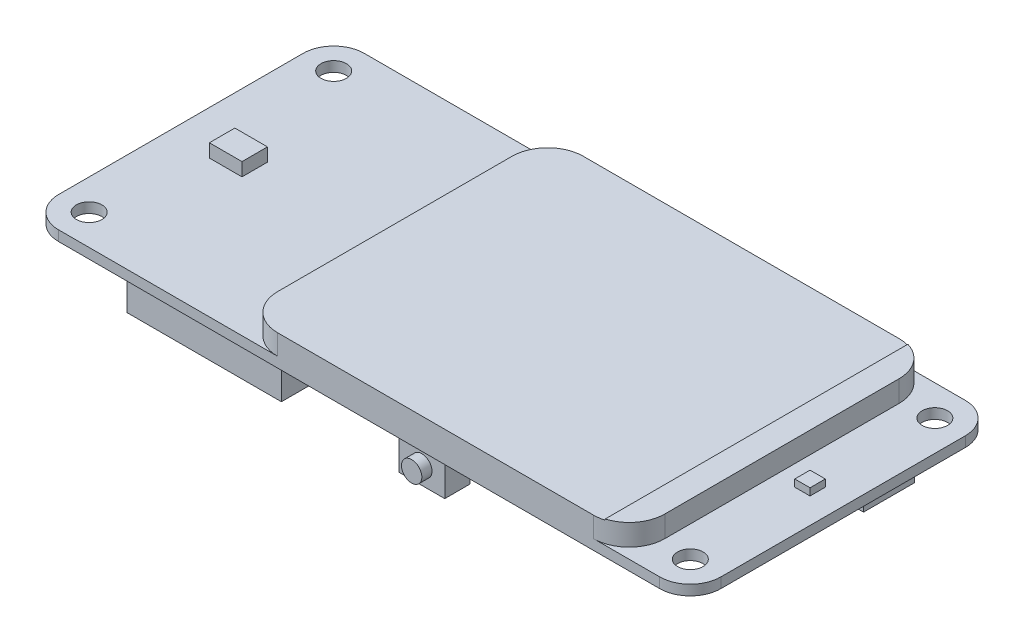
SolidWorks part; units mm, degrees
ref_plane "前视基准面" through (0, 0, 0) normal (0, 0, 1) x (1, 0, 0)
ref_plane "上视基准面" through (0, 0, 0) normal (0, 1, 0) x (1, 0, 0)
ref_plane "右视基准面" through (0, 0, 0) normal (1, 0, 0) x (0, 0, -1)
other "Configuration Table"
sketch "草图1" plane through (0, 0, 0) normal (0, 1, 0) x (1, 0, 0)
  line L1 (-29.5, 15) -> (29.5, 15)
  line L2 (-32.5, 12) -> (-32.5, -12)
  line L3 (-29.5, -15) -> (29.5, -15)
  line L4 (32.5, 12) -> (32.5, -12)
  line L5 (-32.5, 15) -> (32.5, -15) construction
  line L6 (-32.5, -15) -> (32.5, 15) construction
  arc A0 (29.5, -15) -> (32.5, -12) centre (29.5, -12) ccw
  arc A1 (29.5, 15) -> (32.5, 12) centre (29.5, 12) cw
  arc A2 (-32.5, -12) -> (-29.5, -15) centre (-29.5, -12) ccw
  arc A3 (-29.5, 15) -> (-32.5, 12) centre (-29.5, 12) ccw
  circle A4 centre (-29.5, 12) radius 1.25
  circle A5 centre (29.5, 12) radius 1.25
  circle A6 centre (-29.5, -12) radius 1.25
  circle A7 centre (29.5, -12) radius 1.25
  point P0 (0, 0)
  dimension "D3" = 3
  dimension "D4" = 2.5
  dimension "D1" = 65
  dimension "D2" = 30
extrude "board" add sketch "草图1" along normal blind 1
sketch "草图2" plane through (0, 1, 0) normal (0, 1, 0) x (1, 0, 0)
  line L0 (29.5, 15) -> (-29.5, 15) construction
  line L1 (-11.5, 15) -> (26.5, 15)
  line L2 (-11.5, 15) -> (-11.5, -15)
  line L3 (-11.5, -15) -> (26.5, -15)
  line L4 (26.5, 15) -> (26.5, -15)
  line L5 (-29.5, -15) -> (29.5, -15) construction
  line L6 (-32.5, 12) -> (-32.5, -12) construction
  line L7 (32.5, -12) -> (32.5, 12) construction
  dimension "D1" = 6
  dimension "D2" = 21
extrude "screen" add sketch "草图2" along normal blind 2
fillet "screen-radius" radius 3.5 4 edges at (-11.5, 2, -15) (26.5, 2, -15) (26.5, 2, 15) (-11.5, 2, 15)
sketch "草图3" plane through (0, 0, 0) normal (0, -1, 0) x (1, 0, 0)
  line L0 (32.5, 12) -> (32.5, -12) construction
  line L1 (-25.5, -9) -> (25.5, -9)
  line L2 (-25.5, -9) -> (-25.5, -14)
  line L3 (-25.5, -14) -> (25.5, -14)
  line L4 (25.5, -9) -> (25.5, -14)
  line L6 (29.5, -15) -> (-29.5, -15) construction
  dimension "D1" = 5
  dimension "D2" = 51
  dimension "D3" = 7
  dimension "D4" = 1
extrude "plug" add sketch "草图3" along normal blind 7.5
sketch "草图4" plane through (0, 0, 0) normal (0, -1, 0) x (1, 0, 0)
  line L1 (-25.09, 12.68) -> (-9.95, 12.68)
  line L2 (-25.09, 12.68) -> (-25.09, -7.32)
  line L3 (-25.09, -7.32) -> (-9.95, -7.32)
  line L4 (-9.95, 12.68) -> (-9.95, -7.32)
  line L5 (-32.5, -12) -> (-32.5, 12) construction
  line L6 (-29.5, 15) -> (29.5, 15) construction
  dimension "D1" = 15.14
  dimension "D2" = 20
  dimension "D3" = 7.41
  dimension "D4" = 2.32
extrude "speaker" add sketch "草图4" along normal blind 5
sketch "草图5" plane through (0, 0, 0) normal (0, -1, 0) x (1, 0, 0)
  line L0 (-29.5, 15) -> (29.5, 15) construction
  line L1 (3.4, 14.5) -> (7.9, 14.5)
  line L2 (3.4, 14.5) -> (3.4, 12)
  line L3 (3.4, 12) -> (7.9, 12)
  line L4 (7.9, 14.5) -> (7.9, 12)
  line L6 (32.5, 12) -> (32.5, -12) construction
  dimension "D1" = 4.5
  dimension "D2" = 2.5
  dimension "D3" = 0.5
  dimension "D4" = 24.6
extrude "button" add sketch "草图5" along normal blind 3.4
sketch "草图6" plane through (0, 0, 14.5) normal (0, 0, 1) x (1, 0, 0)
  line L0 (7.9, 0) -> (3.4, 0) construction
  line L1 (7.9, -3.4) -> (3.4, -3.4) construction
  circle A0 centre (5.65, -1.7) radius 1
  point P7 (5.65, -3.4)
  dimension "D1" = 2
  dimension "D2" = 1.7
extrude "button-tap" add sketch "草图6" along normal blind 1
sketch "草图7" plane through (0, 1, 0) normal (0, 1, 0) x (1, 0, 0)
  line L1 (28.5, 0.75) -> (30, 0.75)
  line L2 (28.5, 0.75) -> (28.5, -0.75)
  line L3 (28.5, -0.75) -> (30, -0.75)
  line L4 (30, 0.75) -> (30, -0.75)
  line L6 (32.5, -12) -> (32.5, 12) construction
  point P4 (32.5, 0)
  point P5 (30, 0)
  dimension "D1" = 1.5
  dimension "D2" = 1.5
  dimension "D4" = 2.5
extrude "rgb-led" add sketch "草图7" along normal blind 0.7
sketch "草图8" plane through (0, 1, 0) normal (0, 1, 0) x (1, 0, 0)
  line L0 (29.5, 15) -> (23, 15) construction
  line L1 (-25, 1) -> (-28.2, 1)
  line L2 (-25, 1) -> (-25, -1.5)
  line L3 (-25, -1.5) -> (-28.2, -1.5)
  line L4 (-28.2, 1) -> (-28.2, -1.5)
  line L6 (-32.5, 12) -> (-32.5, -12) construction
  dimension "D1" = 3.2
  dimension "D2" = 2.5
  dimension "D3" = 14
  dimension "D4" = 4.3
extrude "mic" add sketch "草图8" along normal blind 1.3
sketch "草图9" plane through (0, 3, 0) normal (0, 1, 0) x (1, 0, 0)
  line L0 (26.5, -11.5) -> (26.5, 11.5) construction
  line L1 (26.5, -11.5) -> (26.5, 11.5)
  line L2 (24, 14.8541) -> (24, -14.8541)
  line L3 (32.5, -12) -> (32.5, 12) construction
  arc A0 (23, -15) -> (26.5, -11.5) centre (23, -11.5) ccw construction
  arc A1 (26.5, 11.5) -> (23, 15) centre (23, 11.5) ccw construction
  arc A2 (26.5, -11.5) -> (24, -14.8541) centre (23, -11.5) cw
  arc A3 (26.5, 11.5) -> (24, 14.8541) centre (23, 11.5) ccw
  dimension "D1" = 8.5
extrude "凸台-拉伸1" add sketch "草图9" along normal blind 0.1
